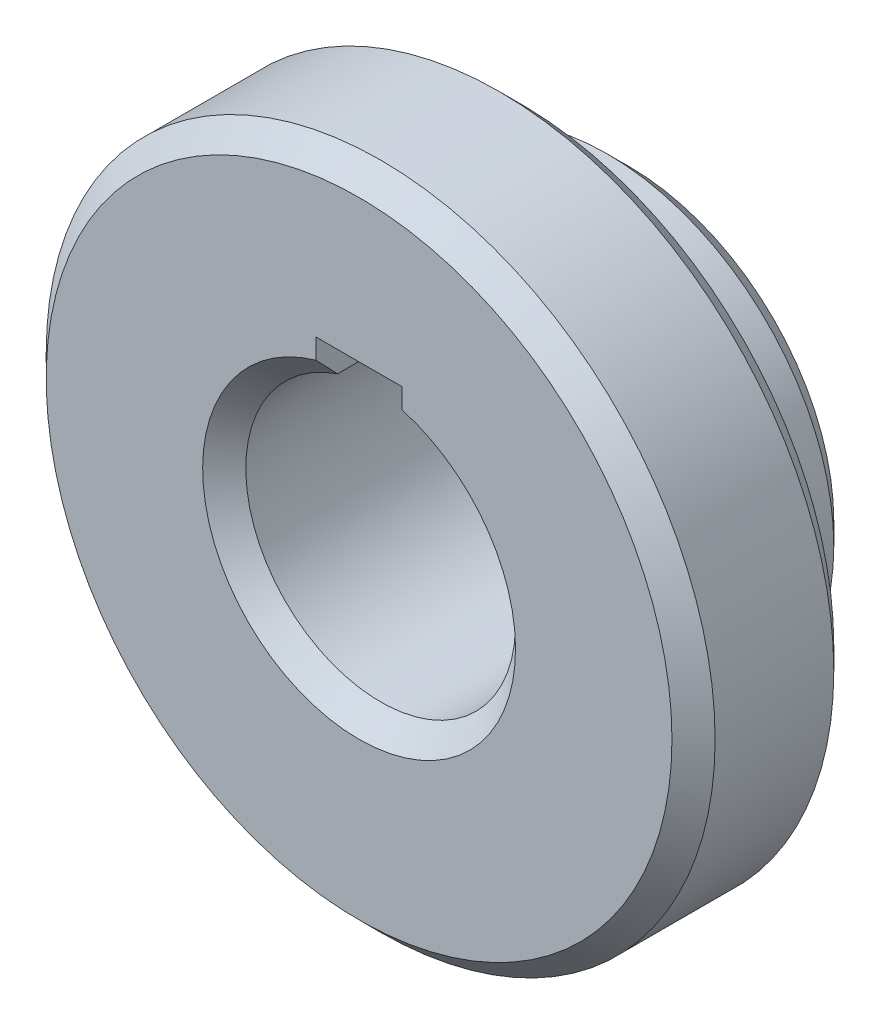
SolidWorks part; units mm, degrees
material "6061 合金"
ref_plane "前视基准面" through (0, 0, 0) normal (0, 0, 1) x (1, 0, 0)
ref_plane "上视基准面" through (0, 0, 0) normal (0, 1, 0) x (1, 0, 0)
ref_plane "右视基准面" through (0, 0, 0) normal (1, 0, 0) x (0, 0, -1)
other "Configuration Table"
sketch "草图1" plane through (0, 0, 0) normal (0, 0, 1) x (1, 0, 0)
  circle A1 centre (0, 0) radius 31
extrude "凸台-拉伸1" add sketch "草图1" against normal blind 15
sketch "草图2" plane through (0, 0, -15) normal (0, 0, -1) x (-1, 0, 0)
  circle A0 centre (0, 0) radius 21
extrude "凸台-拉伸2" add sketch "草图2" along normal blind 10
sketch "草图3" plane through (0, 0, 0) normal (0, 0, 1) x (1, 0, 0)
  circle A0 centre (0, 0) radius 12.5
extrude "切除-拉伸1" cut sketch "草图3" against normal through all
sketch "草图4" plane through (0, 0, 0) normal (0, 0, 1) x (1, 0, 0)
  line L1 (0, 15.8) -> (4, 15.8)
  line L2 (0, 15.8) -> (-4, 15.8)
  line L3 (-4, 15.8) -> (-4, 11.8427)
  line L5 (4, 11.8427) -> (4, 15.8)
  circle A0 centre (0, 0) radius 12.5 construction
  arc A1 (-4, 11.8427) -> (4, 11.8427) centre (0, 0) cw
extrude "切除-拉伸3" cut sketch "草图4" against normal through all
chamfer "倒角1" distance 2 angle 45 1 edges at (31, 0, 0)
chamfer "倒角2" distance 2 angle 45 1 edges at (31, 0, -15)
chamfer "倒角3" distance 2 angle 45 1 edges at (0, -12.5, 0)
chamfer "倒角4" distance 2 angle 45 1 edges at (0, -12.5, -25)
chamfer "倒角5" distance 2 angle 45 1 edges at (-21, 0, -25)
fillet "圆角1" radius 3 1 edges at (-21, 0, -15)
